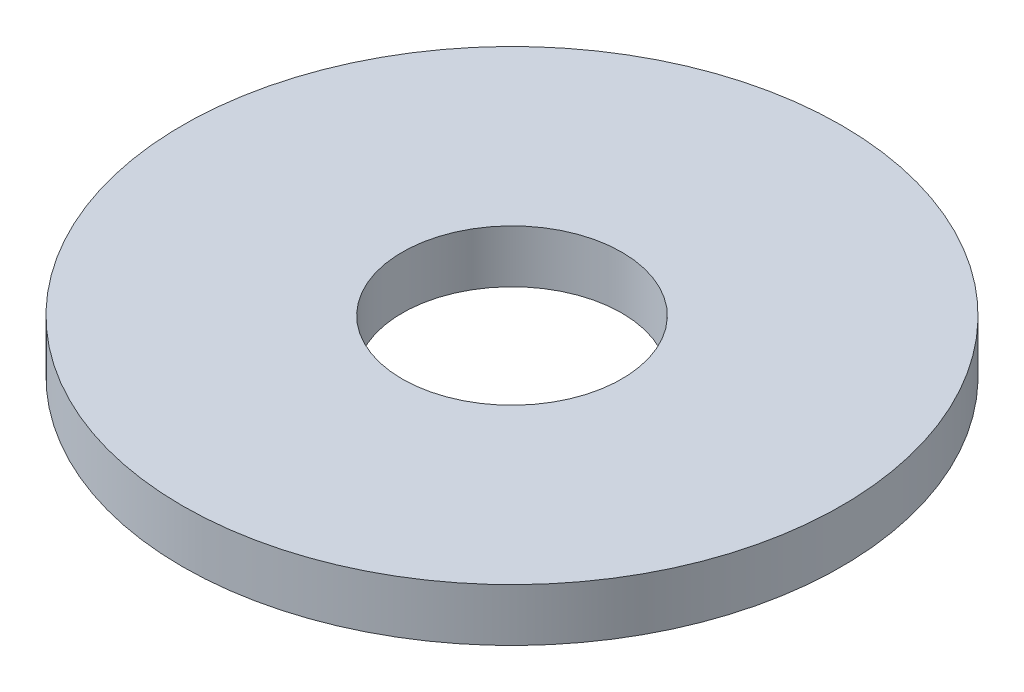
SolidWorks part; units mm, degrees
material "Chrome Stainless Steel"
ref_plane "Front Plane" through (0, 0, 0) normal (0, 0, 1) x (1, 0, 0)
ref_plane "Top Plane" through (0, 0, 0) normal (0, 1, 0) x (1, 0, 0)
ref_plane "Right Plane" through (0, 0, 0) normal (1, 0, 0) x (0, 0, -1)
sketch "Sketch1" plane through (0, 0, 0) normal (0, 1, 0) x (1, 0, 0)
  circle A0 centre (0, 0) radius 2.5
  circle A1 centre (0, 0) radius 7.5
  dimension "D1" = 5
  dimension "D2" = 15
extrude "Boss-Extrude1" add sketch "Sketch1" along normal blind 1.2
